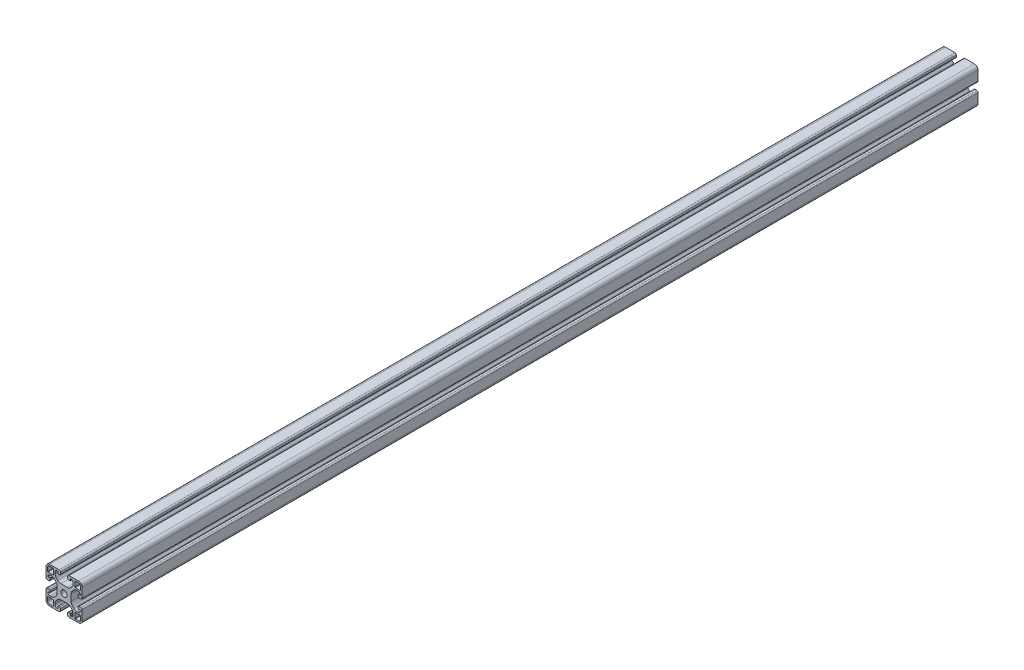
SolidWorks part; units mm, degrees
ref_plane "Plan de face" through (0, 0, 0) normal (0, 0, 1) x (1, 0, 0)
ref_plane "Plan de dessus" through (0, 0, 0) normal (0, 1, 0) x (1, 0, 0)
ref_plane "Plan de droite" through (0, 0, 0) normal (1, 0, 0) x (0, 0, -1)
ref_plane "Plan1" through (0, 0, -30) normal (0, 0, -1) x (-1, 0, 0)
sketch "Esquisse1" plane through (0, 0, -30) normal (0, 0, -1) x (-1, 0, 0)
  line L0 (-4.5, 15) -> (-4.5, 13.5)
  line L1 (-4, 13) -> (-2.5, 13)
  line L2 (-4.5, 10) -> (-5.8076, 10)
  line L3 (-9.3431, 11.4645) -> (-10.7855, 12.9069)
  line L4 (-12.25, 16.4424) -> (-12.25, 23.5576)
  line L5 (-10.7855, 27.0931) -> (-9.3431, 28.5355)
  line L6 (-5.8076, 30) -> (-4.5, 30)
  line L7 (-2.5, 27) -> (-4, 27)
  line L8 (-4.5, 26.5) -> (-4.5, 25)
  line L9 (-3.5, 24) -> (-1.5, 24)
  line L10 (0, 25.5) -> (0, 36)
  line L11 (-4, 40) -> (-14.5, 40)
  line L12 (-16, 38.5) -> (-16, 36.5)
  line L13 (-15, 35.5) -> (-13.5, 35.5)
  line L14 (-13, 36) -> (-13, 37.5)
  line L15 (-10, 35.5) -> (-10, 34.1924)
  line L16 (-11.4645, 30.6569) -> (-12.9069, 29.2145)
  line L17 (-16.4424, 27.75) -> (-23.5576, 27.75)
  line L18 (-27.0931, 29.2145) -> (-28.5355, 30.6569)
  line L19 (-30, 34.1924) -> (-30, 35.5)
  line L20 (-27, 37.5) -> (-27, 36)
  line L21 (-26.5, 35.5) -> (-25, 35.5)
  line L22 (-24, 36.5) -> (-24, 38.5)
  line L23 (-25.5, 40) -> (-36, 40)
  line L24 (-40, 36) -> (-40, 25.5)
  line L25 (-38.5, 24) -> (-36.5, 24)
  line L26 (-35.5, 25) -> (-35.5, 26.5)
  line L27 (-36, 27) -> (-37.5, 27)
  line L28 (-35.5, 30) -> (-34.1924, 30)
  line L29 (-30.6569, 28.5355) -> (-29.2145, 27.0931)
  line L30 (-27.75, 23.5576) -> (-27.75, 16.4424)
  line L31 (-29.2145, 12.9069) -> (-30.6569, 11.4645)
  line L32 (-34.1924, 10) -> (-35.5, 10)
  line L33 (-37.5, 13) -> (-36, 13)
  line L34 (-35.5, 13.5) -> (-35.5, 15)
  line L35 (-36.5, 16) -> (-38.5, 16)
  line L36 (-40, 14.5) -> (-40, 4)
  line L37 (-36, 0) -> (-25.5, 0)
  line L38 (-24, 1.5) -> (-24, 3.5)
  line L39 (-25, 4.5) -> (-26.5, 4.5)
  line L40 (-27, 4) -> (-27, 2.5)
  line L41 (-30, 4.5) -> (-30, 5.8076)
  line L42 (-28.5355, 9.3431) -> (-27.0931, 10.7855)
  line L43 (-23.5576, 12.25) -> (-16.4424, 12.25)
  line L44 (-12.9069, 10.7855) -> (-11.4645, 9.3431)
  line L45 (-10, 5.8076) -> (-10, 4.5)
  line L46 (-13, 2.5) -> (-13, 4)
  line L47 (-13.5, 4.5) -> (-15, 4.5)
  line L48 (-16, 3.5) -> (-16, 1.5)
  line L49 (-14.5, 0) -> (-4, 0)
  line L50 (0, 4) -> (0, 14.5)
  line L51 (-1.5, 16) -> (-3.5, 16)
  line L52 (-4, 1.8) -> (-7.7, 1.8)
  line L53 (-8.2, 2.3) -> (-8.2, 7.7)
  line L54 (-7.7, 8.2) -> (-2.3, 8.2)
  line L55 (-1.8, 7.7) -> (-1.8, 4)
  line L56 (-38.2, 4) -> (-38.2, 7.7)
  line L57 (-37.7, 8.2) -> (-32.3, 8.2)
  line L58 (-31.8, 7.7) -> (-31.8, 2.3)
  line L59 (-32.3, 1.8) -> (-36, 1.8)
  line L60 (-36, 38.2) -> (-32.3, 38.2)
  line L61 (-31.8, 37.7) -> (-31.8, 32.3)
  line L62 (-32.3, 31.8) -> (-37.7, 31.8)
  line L63 (-38.2, 32.3) -> (-38.2, 36)
  line L64 (-1.8, 36) -> (-1.8, 32.3)
  line L65 (-2.3, 31.8) -> (-7.7, 31.8)
  line L66 (-8.2, 32.3) -> (-8.2, 37.7)
  line L67 (-7.7, 38.2) -> (-4, 38.2)
  arc A0 (-4.5, 13.5) -> (-4, 13) centre (-4, 13.5) ccw
  arc A1 (-2.5, 13) -> (-2, 12.5) centre (-2.5, 12.5) cw
  arc A2 (-2, 12.5) -> (-4.5, 10) centre (-4.5, 12.5) cw
  arc A3 (-5.8076, 10) -> (-9.3431, 11.4645) centre (-5.8076, 15) cw
  arc A4 (-10.7855, 12.9069) -> (-12.25, 16.4424) centre (-7.25, 16.4424) cw
  arc A5 (-12.25, 23.5576) -> (-10.7855, 27.0931) centre (-7.25, 23.5576) cw
  arc A6 (-9.3431, 28.5355) -> (-5.8076, 30) centre (-5.8076, 25) cw
  arc A7 (-4.5, 30) -> (-2, 27.5) centre (-4.5, 27.5) cw
  arc A8 (-2, 27.5) -> (-2.5, 27) centre (-2.5, 27.5) cw
  arc A9 (-4, 27) -> (-4.5, 26.5) centre (-4, 26.5) ccw
  arc A10 (-4.5, 25) -> (-3.5, 24) centre (-3.5, 25) ccw
  arc A11 (-1.5, 24) -> (0, 25.5) centre (-1.5, 25.5) ccw
  arc A12 (0, 36) -> (-4, 40) centre (-4, 36) ccw
  arc A13 (-14.5, 40) -> (-16, 38.5) centre (-14.5, 38.5) ccw
  arc A14 (-16, 36.5) -> (-15, 35.5) centre (-15, 36.5) ccw
  arc A15 (-13.5, 35.5) -> (-13, 36) centre (-13.5, 36) ccw
  arc A16 (-13, 37.5) -> (-12.5, 38) centre (-12.5, 37.5) cw
  arc A17 (-12.5, 38) -> (-10, 35.5) centre (-12.5, 35.5) cw
  arc A18 (-10, 34.1924) -> (-11.4645, 30.6569) centre (-15, 34.1924) cw
  arc A19 (-12.9069, 29.2145) -> (-16.4424, 27.75) centre (-16.4424, 32.75) cw
  arc A20 (-23.5576, 27.75) -> (-27.0931, 29.2145) centre (-23.5576, 32.75) cw
  arc A21 (-28.5355, 30.6569) -> (-30, 34.1924) centre (-25, 34.1924) cw
  arc A22 (-30, 35.5) -> (-27.5, 38) centre (-27.5, 35.5) cw
  arc A23 (-27.5, 38) -> (-27, 37.5) centre (-27.5, 37.5) cw
  arc A24 (-27, 36) -> (-26.5, 35.5) centre (-26.5, 36) ccw
  arc A25 (-25, 35.5) -> (-24, 36.5) centre (-25, 36.5) ccw
  arc A26 (-24, 38.5) -> (-25.5, 40) centre (-25.5, 38.5) ccw
  arc A27 (-36, 40) -> (-40, 36) centre (-36, 36) ccw
  arc A28 (-40, 25.5) -> (-38.5, 24) centre (-38.5, 25.5) ccw
  arc A29 (-36.5, 24) -> (-35.5, 25) centre (-36.5, 25) ccw
  arc A30 (-35.5, 26.5) -> (-36, 27) centre (-36, 26.5) ccw
  arc A31 (-37.5, 27) -> (-38, 27.5) centre (-37.5, 27.5) cw
  arc A32 (-38, 27.5) -> (-35.5, 30) centre (-35.5, 27.5) cw
  arc A33 (-34.1924, 30) -> (-30.6569, 28.5355) centre (-34.1924, 25) cw
  arc A34 (-29.2145, 27.0931) -> (-27.75, 23.5576) centre (-32.75, 23.5576) cw
  arc A35 (-27.75, 16.4424) -> (-29.2145, 12.9069) centre (-32.75, 16.4424) cw
  arc A36 (-30.6569, 11.4645) -> (-34.1924, 10) centre (-34.1924, 15) cw
  arc A37 (-35.5, 10) -> (-38, 12.5) centre (-35.5, 12.5) cw
  arc A38 (-38, 12.5) -> (-37.5, 13) centre (-37.5, 12.5) cw
  arc A39 (-36, 13) -> (-35.5, 13.5) centre (-36, 13.5) ccw
  arc A40 (-35.5, 15) -> (-36.5, 16) centre (-36.5, 15) ccw
  arc A41 (-38.5, 16) -> (-40, 14.5) centre (-38.5, 14.5) ccw
  arc A42 (-40, 4) -> (-36, 0) centre (-36, 4) ccw
  arc A43 (-25.5, 0) -> (-24, 1.5) centre (-25.5, 1.5) ccw
  arc A44 (-24, 3.5) -> (-25, 4.5) centre (-25, 3.5) ccw
  arc A45 (-26.5, 4.5) -> (-27, 4) centre (-26.5, 4) ccw
  arc A46 (-27, 2.5) -> (-27.5, 2) centre (-27.5, 2.5) cw
  arc A47 (-27.5, 2) -> (-30, 4.5) centre (-27.5, 4.5) cw
  arc A48 (-30, 5.8076) -> (-28.5355, 9.3431) centre (-25, 5.8076) cw
  arc A49 (-27.0931, 10.7855) -> (-23.5576, 12.25) centre (-23.5576, 7.25) cw
  arc A50 (-16.4424, 12.25) -> (-12.9069, 10.7855) centre (-16.4424, 7.25) cw
  arc A51 (-11.4645, 9.3431) -> (-10, 5.8076) centre (-15, 5.8076) cw
  arc A52 (-10, 4.5) -> (-12.5, 2) centre (-12.5, 4.5) cw
  arc A53 (-12.5, 2) -> (-13, 2.5) centre (-12.5, 2.5) cw
  arc A54 (-13, 4) -> (-13.5, 4.5) centre (-13.5, 4) ccw
  arc A55 (-15, 4.5) -> (-16, 3.5) centre (-15, 3.5) ccw
  arc A56 (-16, 1.5) -> (-14.5, 0) centre (-14.5, 1.5) ccw
  arc A57 (-4, 0) -> (0, 4) centre (-4, 4) ccw
  arc A58 (0, 14.5) -> (-1.5, 16) centre (-1.5, 14.5) ccw
  arc A59 (-3.5, 16) -> (-4.5, 15) centre (-3.5, 15) ccw
  circle A60 centre (-20, 20) radius 3.4
  arc A61 (-1.8, 4) -> (-4, 1.8) centre (-4, 4) cw
  arc A62 (-7.7, 1.8) -> (-8.2, 2.3) centre (-7.7, 2.3) cw
  arc A63 (-8.2, 7.7) -> (-7.7, 8.2) centre (-7.7, 7.7) cw
  arc A64 (-2.3, 8.2) -> (-1.8, 7.7) centre (-2.3, 7.7) cw
  arc A65 (-36, 1.8) -> (-38.2, 4) centre (-36, 4) cw
  arc A66 (-38.2, 7.7) -> (-37.7, 8.2) centre (-37.7, 7.7) cw
  arc A67 (-32.3, 8.2) -> (-31.8, 7.7) centre (-32.3, 7.7) cw
  arc A68 (-31.8, 2.3) -> (-32.3, 1.8) centre (-32.3, 2.3) cw
  arc A69 (-38.2, 36) -> (-36, 38.2) centre (-36, 36) cw
  arc A70 (-32.3, 38.2) -> (-31.8, 37.7) centre (-32.3, 37.7) cw
  arc A71 (-31.8, 32.3) -> (-32.3, 31.8) centre (-32.3, 32.3) cw
  arc A72 (-37.7, 31.8) -> (-38.2, 32.3) centre (-37.7, 32.3) cw
  arc A73 (-4, 38.2) -> (-1.8, 36) centre (-4, 36) cw
  arc A74 (-1.8, 32.3) -> (-2.3, 31.8) centre (-2.3, 32.3) cw
  arc A75 (-7.7, 31.8) -> (-8.2, 32.3) centre (-7.7, 32.3) cw
  arc A76 (-8.2, 37.7) -> (-7.7, 38.2) centre (-7.7, 37.7) cw
extrude "Boss.-Extru.1" add sketch "Esquisse1" against normal blind 990
